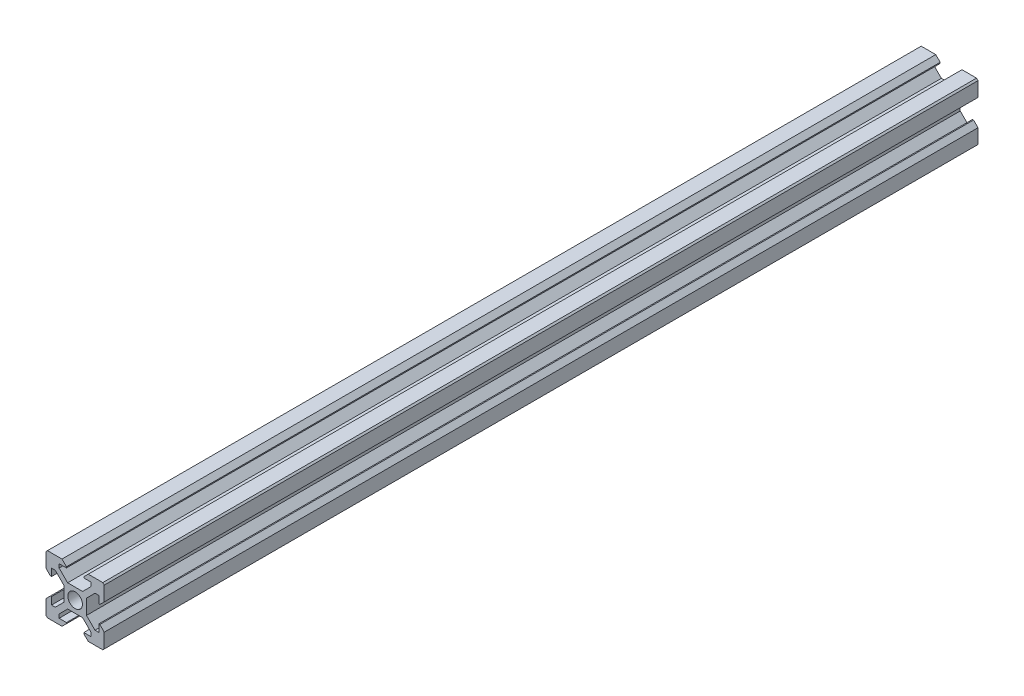
SolidWorks part; units mm, degrees
material "6061 Alloy"
ref_plane "Front Plane" through (0, 0, 0) normal (0, 0, 1) x (1, 0, 0)
ref_plane "Top Plane" through (0, 0, 0) normal (0, 1, 0) x (1, 0, 0)
ref_plane "Right Plane" through (0, 0, 0) normal (1, 0, 0) x (0, 0, -1)
sketch "Sketch1" plane through (0, 0, 0) normal (0, 0, 1) x (1, 0, 0)
  line L0 (15.6876, 55.3211) -> (115.0437, 55.3211) construction
  line L1 (5.5, 6.8294) -> (2.5706, 3.9)
  line L2 (0, 3.9) -> (0, 2.5)
  line L3 (10, 10) -> (1.7678, 1.7678)
  line L4 (10, 10) -> (4.5, 10)
  line L5 (1.7678, 1.7678) -> (3.9, 3.9) construction
  line L6 (10, -10) -> (-10, 10) construction
  line L7 (10, 10) -> (1.7678, 1.7678) construction
  line L8 (0, 0) -> (-10, -10) construction
  line L10 (0, 3.9) -> (2.5706, 3.9)
  line L12 (-3.9, -3.9) -> (0, 0) construction
  line L13 (-3.9, 3.9) -> (3.9, -3.9) construction
  line L14 (5.5, 6.8294) -> (5.5, 8.12)
  line L15 (5.5, 8.12) -> (2.62, 8.12)
  line L16 (2.62, 8.12) -> (4.5, 10)
  line L17 (0, 2.5) -> (0, 16.7618) construction
  arc A0 (1.7678, 1.7678) -> (0, 2.5) centre (0, 0) ccw
  point P2 (0, 0)
  point P7 (0, 0)
  dimension "D3" = 45
  dimension "D4" = 6.1
  dimension "D8" = 5
  dimension "D1" = 20
  dimension "D2" = 11
  dimension "D5" = 1.88
  dimension "D6" = 9
  dimension "D7" = 0.94
  dimension "D9" = 3.9
extrude "Boss-Extrude1" add sketch "Sketch1" along normal blind 300
chamfer "Chamfer2" distance 0.5 angle 45 1 edges at (2.62, 8.12, 150)
mirror "Mirror1" about plane through (10, 10, 300) normal (-0.7071, 0.7071, 0) of bodies 102
chamfer "Chamfer1" distance 0.5 angle 45 1 edges at (10, 10, 150)
mirror "Mirror4" about plane through (0, 3.9, 300) normal (1, 0, 0) of bodies 103 104
mirror "Mirror5" about plane through (-3.9, 0, 300) normal (0, 1, 0) of bodies 105
